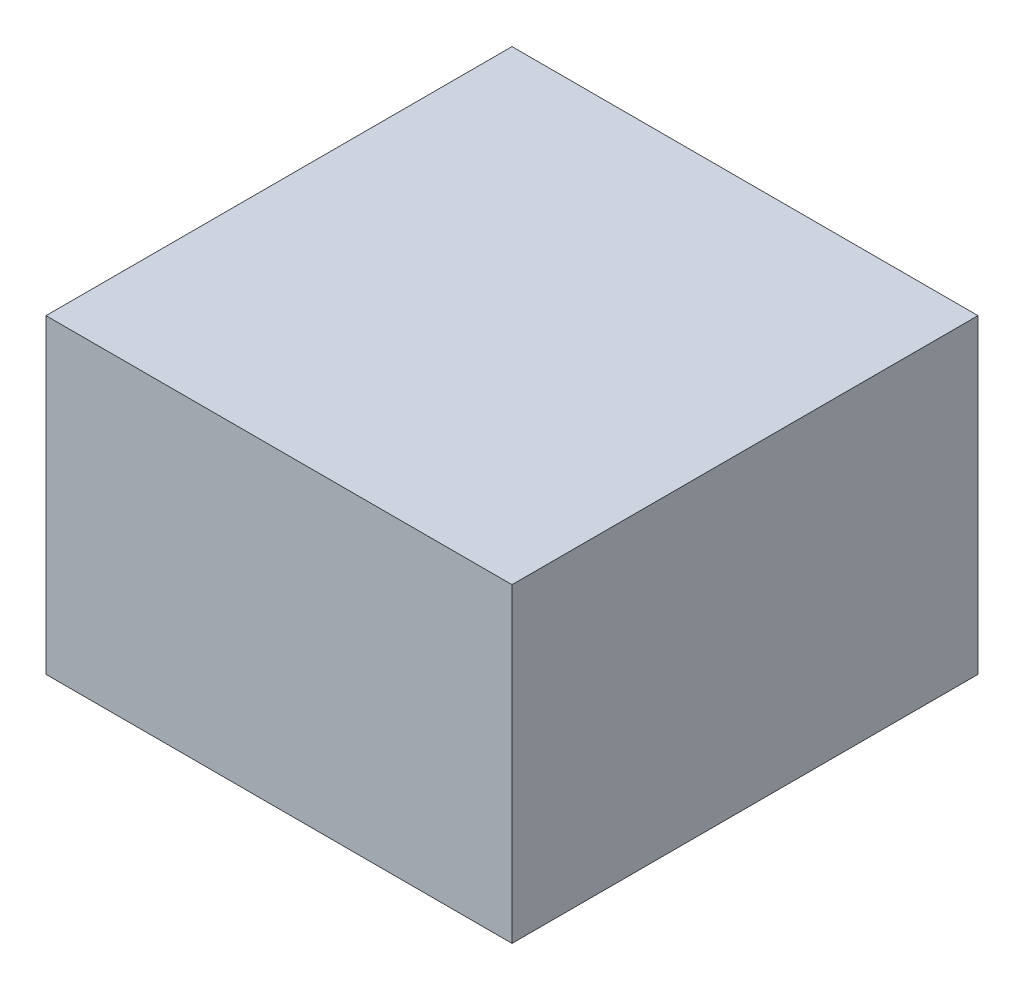
SolidWorks part; units mm, degrees
material "Caucho de silicio"
ref_plane "Alzado" through (0, 0, 0) normal (0, 0, 1) x (1, 0, 0)
ref_plane "Planta" through (0, 0, 0) normal (0, 1, 0) x (1, 0, 0)
ref_plane "Vista lateral" through (0, 0, 0) normal (1, 0, 0) x (0, 0, -1)
sketch "Croquis1" plane through (0, 0, 0) normal (0, 1, 0) x (1, 0, 0)
  line L1 (-7.5, -7.5) -> (7.5, -7.5)
  line L2 (-7.5, -7.5) -> (-7.5, 7.5)
  line L3 (-7.5, 7.5) -> (7.5, 7.5)
  line L4 (7.5, -7.5) -> (7.5, 7.5)
  line L5 (-7.5, -7.5) -> (7.5, 7.5) construction
  line L6 (-7.5, 7.5) -> (7.5, -7.5) construction
  point P0 (0, 0)
  dimension "D1" = 15
  dimension "D2" = 15
extrude "Saliente-Extruir1" add sketch "Croquis1" along normal blind 10
